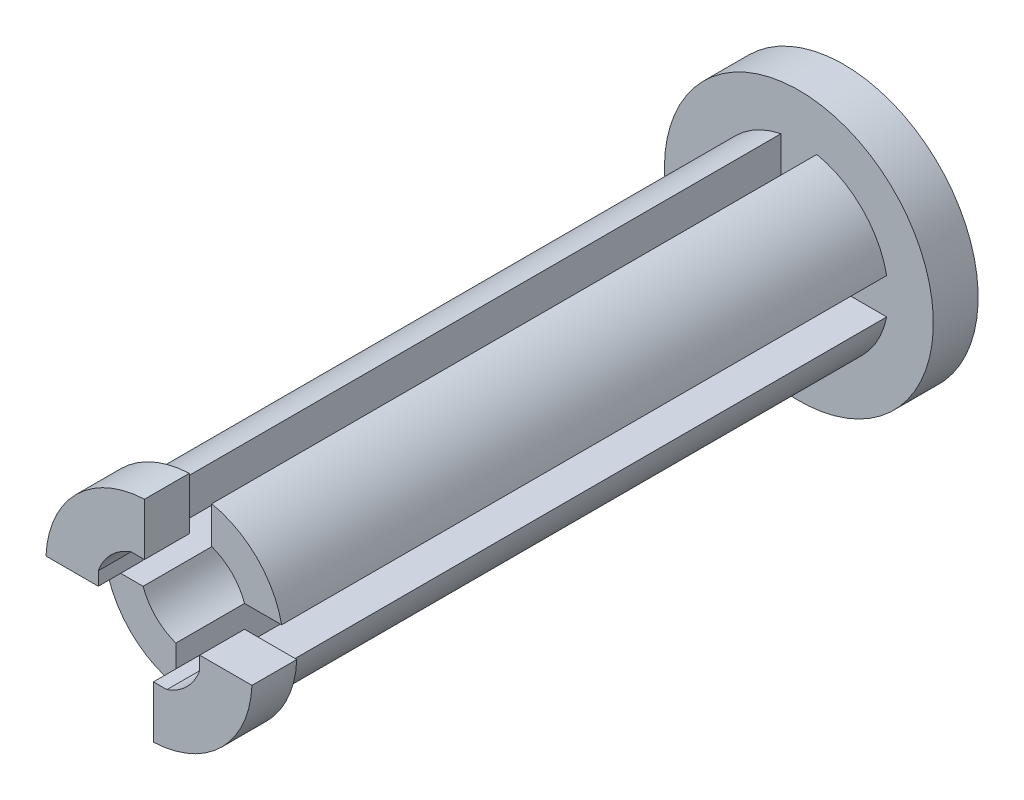
SolidWorks part; units mm, degrees
ref_plane "Front Plane" through (0, 0, 0) normal (0, 0, 1) x (1, 0, 0)
ref_plane "Top Plane" through (0, 0, 0) normal (0, 1, 0) x (1, 0, 0)
ref_plane "Right Plane" through (0, 0, 0) normal (1, 0, 0) x (0, 0, -1)
sketch "Sketch1" plane through (0, 0, 0) normal (0, 0, 1) x (1, 0, 0)
  circle A0 centre (0, 0) radius 2
  dimension "D1" = 4
extrude "Boss-Extrude1" add sketch "Sketch1" along normal blind 13.5
sketch "Sketch2" plane through (0, 0, 13.5) normal (0, 0, 1) x (1, 0, 0)
  circle A0 centre (0, 0) radius 1.2
  dimension "D1" = 2.4
extrude "Cut-Extrude1" cut sketch "Sketch2" against normal through all
sketch "Sketch3" plane through (0, 0, 13.5) normal (0, 0, 1) x (1, 0, 0)
  line L0 (0, -3.2963) -> (0, 3.2963)
  line L1 (-3.5035, 0) -> (3.5035, 0)
  line L2 (0.4, -3.2963) -> (0.4, 3.2963)
  line L3 (-3.5035, -0.4) -> (3.5035, -0.4)
  line L4 (-0.4, -3.2963) -> (-0.4, 3.2963)
  line L5 (-3.5035, 0.4) -> (3.5035, 0.4)
  line L6 (-0.4, 3.2963) -> (0.4, 3.2963)
  line L7 (3.5035, 0.4) -> (3.5035, -0.4)
  line L8 (-3.5035, 0.4) -> (-3.5035, -0.4)
  line L9 (0.4, -3.2963) -> (-0.4, -3.2963)
  circle A2 centre (0, 0) radius 2
  circle A3 centre (0, 0) radius 2
  point P4 (0, 0)
  point P8 (0, 0)
  dimension "D1" = 0
  dimension "D2" = 0.4
  dimension "D3" = 0.4
extrude "Cut-Extrude3" cut sketch "Sketch3" against normal through all contours L8 L2 L3 L0 | L6 L0 L3 L2 | L4 L8 L0 L3 | L4 L5 L0 L8 | L0 L5 L2 L8 | L5 L8 L1 L3 | L8 L3 L1 | L3 L2 L8 L0 | L4 L3 L0 L8 | L3 L8 L1 | L5 L3 L1 L8
sketch "Sketch4" plane through (0, 0, 13.5) normal (0, 0, 1) x (1, 0, 0)
  line L10 (-2.2978, 0.1) -> (-0.8944, 0.1)
  line L11 (-0.1, 0.8944) -> (-0.1, 2.2978)
  line L12 (-2.2978, 0.1) -> (-1.1314, 0.1)
  line L13 (-0.1, 1.1314) -> (-0.1, 2.2978)
  line L16 (-1.1314, 0.4) -> (-1.1314, 0.1)
  line L17 (-0.4, 1.1314) -> (-0.1, 1.1314)
  line L24 (0.1, -0.8944) -> (0.1, -2.2978)
  line L25 (2.2978, -0.1) -> (0.8944, -0.1)
  line L26 (0.1, -1.1314) -> (0.1, -2.2978)
  line L27 (2.2978, -0.1) -> (1.1314, -0.1)
  line L28 (1.1314, -0.4) -> (1.1314, -0.1)
  line L29 (0.4, -1.1314) -> (0.1, -1.1314)
  arc A10 (-0.1, 2.2978) -> (-2.2978, 0.1) centre (0, 0) ccw
  arc A11 (-0.1, 0.8944) -> (-0.8944, 0.1) centre (0, 0) ccw
  arc A12 (-0.1, 2.2978) -> (-2.2978, 0.1) centre (0, 0) ccw
  arc A24 (0.1, -2.2978) -> (2.2978, -0.1) centre (0, 0) ccw
  arc A25 (0.1, -0.8944) -> (0.8944, -0.1) centre (0, 0) ccw
  arc A26 (0.1, -2.2978) -> (2.2978, -0.1) centre (0, 0) ccw
  arc A28 (-0.4, 1.1314) -> (-1.1314, 0.4) centre (0, 0) ccw
  arc A29 (-0.4, 1.1314) -> (-1.1314, 0.4) centre (0, 0) ccw
  arc A31 (0.4, -1.1314) -> (1.1314, -0.4) centre (0, 0) ccw
  arc A34 (0.4, -1.1314) -> (1.1314, -0.4) centre (0, 0) ccw
  dimension "D1" = 0.3
  dimension "D2" = 0
  dimension "D3" = 0.3
  dimension "D4" = 0
extrude "Boss-Extrude2" add sketch "Sketch4" along normal blind 1
sketch "Sketch5" plane through (0, 0, 0) normal (0, 0, -1) x (-1, 0, 0)
  circle A0 centre (0, 0) radius 3
  dimension "D1" = 6
extrude "Boss-Extrude3" add sketch "Sketch5" along normal blind 1
